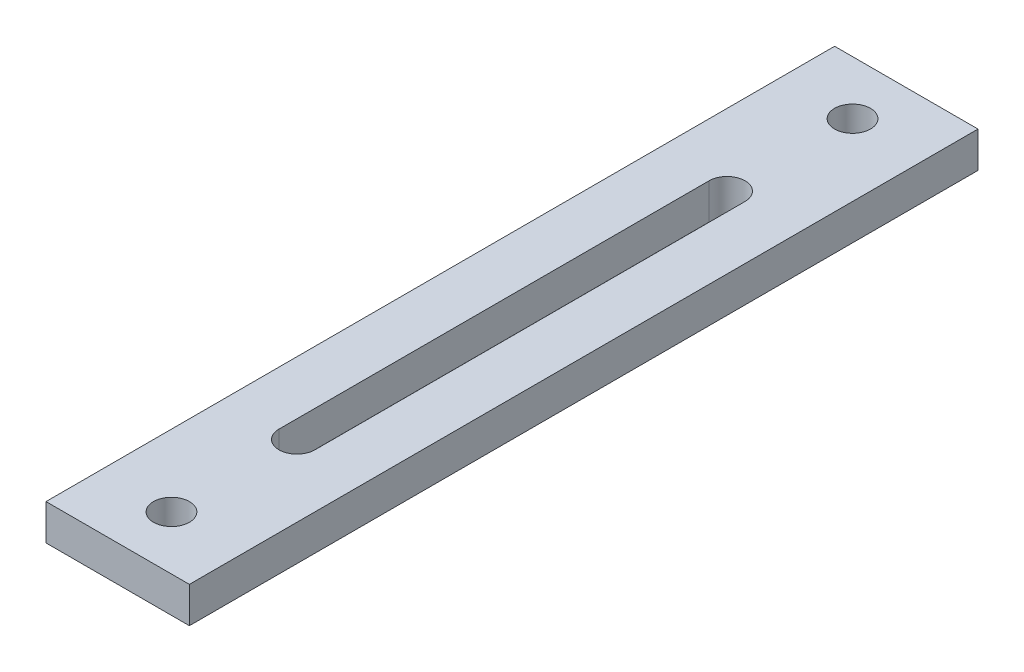
SolidWorks part; units mm, degrees
ref_plane "Front Plane" through (0, 0, 0) normal (0, 0, 1) x (1, 0, 0)
ref_plane "Top Plane" through (0, 0, 0) normal (0, 1, 0) x (1, 0, 0)
ref_plane "Right Plane" through (0, 0, 0) normal (1, 0, 0) x (0, 0, -1)
sketch "Sketch1" plane through (0, 0, 0) normal (0, 1, 0) x (1, 0, 0)
  line L0 (0, -60.325) -> (0, 60.325) construction
  line L1 (-12.7, -69.85) -> (12.7, -69.85)
  line L2 (-12.7, -69.85) -> (-12.7, 69.85)
  line L3 (-12.7, 69.85) -> (12.7, 69.85)
  line L4 (12.7, -69.85) -> (12.7, 69.85)
  line L5 (-12.7, -69.85) -> (12.7, 69.85) construction
  line L6 (-12.7, 69.85) -> (12.7, -69.85) construction
  line L7 (0, -38.1) -> (0, 38.1) construction
  line L8 (-3.1826, -38.1) -> (-3.1826, 38.1)
  line L9 (3.1826, -38.1) -> (3.1826, 38.1)
  arc A0 (-3.1826, -38.1) -> (3.1826, -38.1) centre (0, -38.1) ccw
  arc A1 (3.1826, 38.1) -> (-3.1826, 38.1) centre (0, 38.1) ccw
  circle A2 centre (0, 60.325) radius 3.1826
  circle A3 centre (0, -60.325) radius 3.1826
  point P0 (0, 0)
  point P9 (0, 0)
  point P10 (0, 0)
  dimension "D3" = 6.3652
  dimension "D4" = 6.3652
  dimension "D1" = 25.4
  dimension "D2" = 139.7
  dimension "D5" = 9.525
  dimension "D6" = 76.2
extrude "Boss-Extrude1" add sketch "Sketch1" along normal blind 6.35
